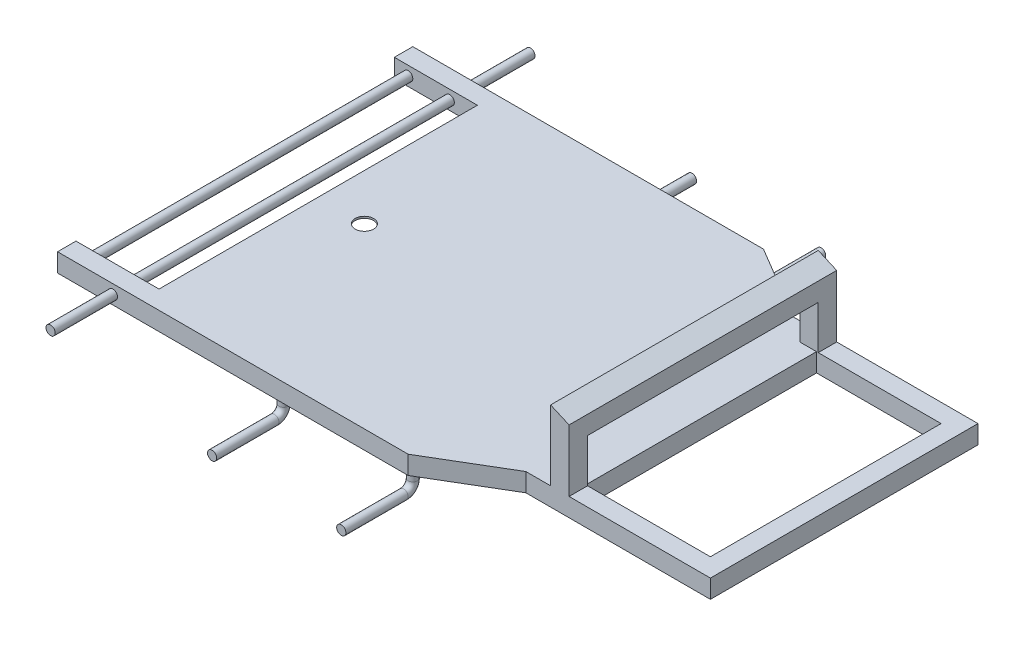
SolidWorks part; units mm, degrees
ref_plane "Front Plane" through (0, 0, 0) normal (0, 0, 1) x (1, 0, 0)
ref_plane "Top Plane" through (0, 0, 0) normal (0, 1, 0) x (1, 0, 0)
ref_plane "Right Plane" through (0, 0, 0) normal (1, 0, 0) x (0, 0, -1)
sketch "Sketch1" plane through (0, 0, 0) normal (0, 1, 0) x (1, 0, 0)
  line L0 (450.4334, 0) -> (-450.4334, 0) construction
  line L1 (0, 292.4073) -> (0, -292.4073) construction
  line L2 (-330, -192.5) -> (-330, 192.5) construction
  line L3 (330, 145) -> (330, -145) construction
  line L4 (-330, 192.5) -> (50, 192.5)
  line L5 (50, 192.5) -> (130, 145)
  line L6 (130, 145) -> (330, 145)
  line L7 (-330, 172.5) -> (44.5099, 172.5)
  line L8 (44.5099, 172.5) -> (124.5099, 125)
  line L9 (124.5099, 125) -> (310, 125)
  line L10 (-330, 192.5) -> (-330, 172.5)
  line L11 (330, 145) -> (330, 125)
  line L12 (130, -145) -> (330, -145)
  line L13 (50, -192.5) -> (130, -145)
  line L14 (-330, -192.5) -> (50, -192.5)
  line L15 (-330, -192.5) -> (-330, -172.5)
  line L16 (-330, -172.5) -> (44.5099, -172.5)
  line L17 (44.5099, -172.5) -> (124.5099, -125)
  line L18 (124.5099, -125) -> (310, -125)
  line L19 (330, -145) -> (330, -125)
  line L20 (124.5099, 125) -> (330, 125) construction
  line L22 (310, 125) -> (310, -125)
  line L24 (330, 125) -> (330, -125)
  point P4 (0, 0)
  point P8 (0, 0)
  point P10 (-330, 0)
  point P13 (330, 0)
  dimension "D1" = 330
  dimension "D2" = 385
  dimension "D3" = 290
  dimension "D4" = 330
  dimension "D5" = 380
  dimension "D6" = 200
  dimension "D7" = 20
  dimension "D8" = 20
  dimension "D9" = 20
extrude "Boss-Extrude1" add sketch "Sketch1" along normal mid plane 20
sketch "Sketch2" plane through (0, 0, 0) normal (0, 0, 1) x (1, 0, 0)
  line L0 (0, 0) -> (-330, 0) construction
  line L1 (-330, 10) -> (-330, -10) construction
  line L2 (-330, -10) -> (50, -10) construction
  line L3 (-240, 10) -> (-220, 10)
  line L4 (-240, 10) -> (-240, -10)
  line L5 (-240, -10) -> (-220, -10)
  line L6 (-220, 10) -> (-220, -10)
  line L7 (-240, 10) -> (-220, -10) construction
  line L8 (-240, -10) -> (-220, 10) construction
  line L9 (-270, 3.4817) -> (-270, -3.4817) construction
  line L10 (0, 0) -> (330, 0) construction
  line L11 (330, 10) -> (330, -10) construction
  line L13 (155, 10) -> (175, 10)
  line L14 (155, 10) -> (155, -10)
  line L15 (155, -10) -> (175, -10)
  line L16 (175, 10) -> (175, -10)
  line L17 (155, 10) -> (175, -10) construction
  line L18 (155, -10) -> (175, 10) construction
  circle A0 centre (-315, 0) radius 5
  point P8 (-230, 0)
  point P17 (-270, 0)
  point P20 (165, 0)
  dimension "D2" = 10
  dimension "D1" = 315
  dimension "D3" = 45
  dimension "D4" = 40
  dimension "D5" = 20
  dimension "D6" = 20
  dimension "D7" = 20
extrude "Boss-Extrude2" add sketch "Sketch2" along normal mid plane 350
sketch "Sketch3" plane through (0, 0, 0) normal (0, 0, 1) x (1, 0, 0)
  line L0 (0, 0) -> (-315, 0) construction
  circle A0 centre (-270, 0) radius 5
  dimension "D3" = 10
  dimension "D1" = 315
  dimension "D2" = 45
extrude "Boss-Extrude3" add sketch "Sketch3" along normal mid plane 520
sketch "Sketch4" plane through (0, -10, 0) normal (0, -1, 0) x (1, 0, 0)
  line L0 (-270, 260) -> (-270, -260) construction
  line L1 (-265, 260) -> (-275, 260) construction
  line L2 (-275, -260) -> (-265, -260) construction
  line L3 (-330, 182.5) -> (50.8979, 182.5) construction
  line L4 (-330, 172.5) -> (-330, 192.5) construction
  circle A0 centre (-95, 182.5) radius 5
  circle A1 centre (45, 182.5) radius 5
  dimension "D1" = 10
  dimension "D2" = 10
  dimension "D3" = 175
  dimension "D4" = 140
sketch3d "3DSketch1"
  line L0 (-95, -10, 182.5) -> (-95, -20, 182.5)
  line L1 (-95, -30, 192.5) -> (-95, -30, 260)
  line L2 (45, -10, 182.5) -> (45, -20, 182.5)
  line L3 (45, -30, 192.5) -> (45, -30, 260)
  arc A0 (45, -20, 182.5) -> (45, -30, 192.5) centre (45, -20, 192.5) ccw
  arc A1 (-95, -20, 182.5) -> (-95, -30, 192.5) centre (-95, -20, 192.5) ccw
  point P10 (45, -30, 182.5)
  point P11 (35, -20, 192.5)
  point P14 (-95, -30, 182.5)
  point P15 (-105, -20, 192.5)
  dimension "D5" = 10
  dimension "D1" = 77.5
  dimension "D2" = 77.5
  dimension "D3" = 20
  dimension "D4" = 20
sweep "Sweep1" add profiles "Sketch4" path "3DSketch1"
mirror "Mirror1" about plane through (0, 0, 0) normal (0, 0, 1) of "Sweep1"
sketch "Sketch5" plane through (175, 0, 0) normal (1, 0, 0) x (0, 0, -1)
  line L1 (-175, 10) -> (-145, 10)
  line L2 (-175, 10) -> (-175, -10)
  line L3 (-175, -10) -> (-145, -10)
  line L4 (-145, 10) -> (-145, -10)
  line L5 (145, 10) -> (175, 10)
  line L6 (145, 10) -> (145, -10)
  line L7 (145, -10) -> (175, -10)
  line L8 (175, 10) -> (175, -10)
extrude "Cut-Extrude1" cut sketch "Sketch5" against normal up to surface (20 mm away) up to face at (155, 0, 160)
sketch "Sketch6" plane through (0, 10, 0) normal (0, 1, 0) x (1, 0, 0)
  line L0 (-220, -172.5) -> (-220, 172.5) construction
  line L1 (44.5099, -172.5) -> (-220, -172.5) construction
  line L2 (124.5099, -125) -> (44.5099, -172.5) construction
  line L3 (155, -125) -> (124.5099, -125) construction
  line L4 (155, -125) -> (155, 125) construction
  line L5 (124.5099, 125) -> (155, 125) construction
  line L6 (44.5099, 172.5) -> (124.5099, 125) construction
  line L7 (-220, 172.5) -> (44.5099, 172.5) construction
  line L8 (-220, -172.5) -> (-220, 172.5)
  line L9 (44.5099, -172.5) -> (-220, -172.5)
  line L10 (124.5099, -125) -> (44.5099, -172.5)
  line L11 (155, -125) -> (124.5099, -125)
  line L12 (155, -125) -> (155, 125)
  line L13 (124.5099, 125) -> (155, 125)
  line L14 (44.5099, 172.5) -> (124.5099, 125)
  line L15 (-220, 172.5) -> (44.5099, 172.5)
extrude "Boss-Extrude4" add sketch "Sketch6" against normal blind 2
sketch "Sketch7" plane through (0, 10, 0) normal (0, 1, 0) x (1, 0, 0)
  line L0 (0, 0) -> (-320, 0) construction
  line L1 (-320, 172.5) -> (-320, -172.5) construction
  circle A0 centre (-190, 0) radius 10
  dimension "D1" = 20
  dimension "D2" = 190
extrude "Cut-Extrude2" cut sketch "Sketch7" against normal blind 30
sketch "Sketch8" plane through (0, 10, 0) normal (0, 1, 0) x (1, 0, 0)
  line L1 (330, 145) -> (130, 145) construction
  line L2 (130, -145) -> (330, -145) construction
  line L3 (156.85, 145) -> (156.85, -145) construction
  line L5 (175, -125) -> (175, 125) construction
  line L7 (156.85, 145) -> (176.85, 145)
  line L8 (156.85, 145) -> (156.85, -145)
  line L9 (156.85, -145) -> (176.85, -145)
  line L10 (176.85, 145) -> (176.85, -145)
  dimension "D2" = 18.15
  dimension "D3" = 20
extrude "Boss-Extrude5" add sketch "Sketch8" along normal blind 75.92
sketch "Sketch9" plane through (0, 0, 145) normal (0, 0, 1) x (1, 0, 0)
  line L0 (176.85, 10) -> (330, 10) construction
  line L4 (156.85, 85.92) -> (330, 10)
  line L5 (156.85, 85.92) -> (176.85, 85.92)
  line L6 (176.85, 85.92) -> (330, 10)
  line L7 (330, 10) -> (330, -10) construction
  point P0 (329.9118, 10)
  point P9 (0, 0)
extrude "Cut-Extrude3" cut sketch "Sketch9" against normal up to surface (290 mm away) up to face at (198.425, 23.98, -145)
sketch "Sketch10" plane through (176.85, 0, 0) normal (1, 0, 0) x (0, 0, -1)
  line L0 (-125, 10) -> (125, 10) construction
  line L1 (-125, 10) -> (125, 10)
  line L2 (-125, 10) -> (-125, 57.1507)
  line L3 (-125, 57.1507) -> (125, 57.1507)
  line L4 (125, 57.1507) -> (125, 10)
  line L6 (145, 77.1507) -> (-145, 77.1507) construction
  dimension "D1" = 20
extrude "Cut-Extrude4" cut sketch "Sketch10" against normal up to surface (20 mm away) up to face at (156.85, 47.96, 0)
